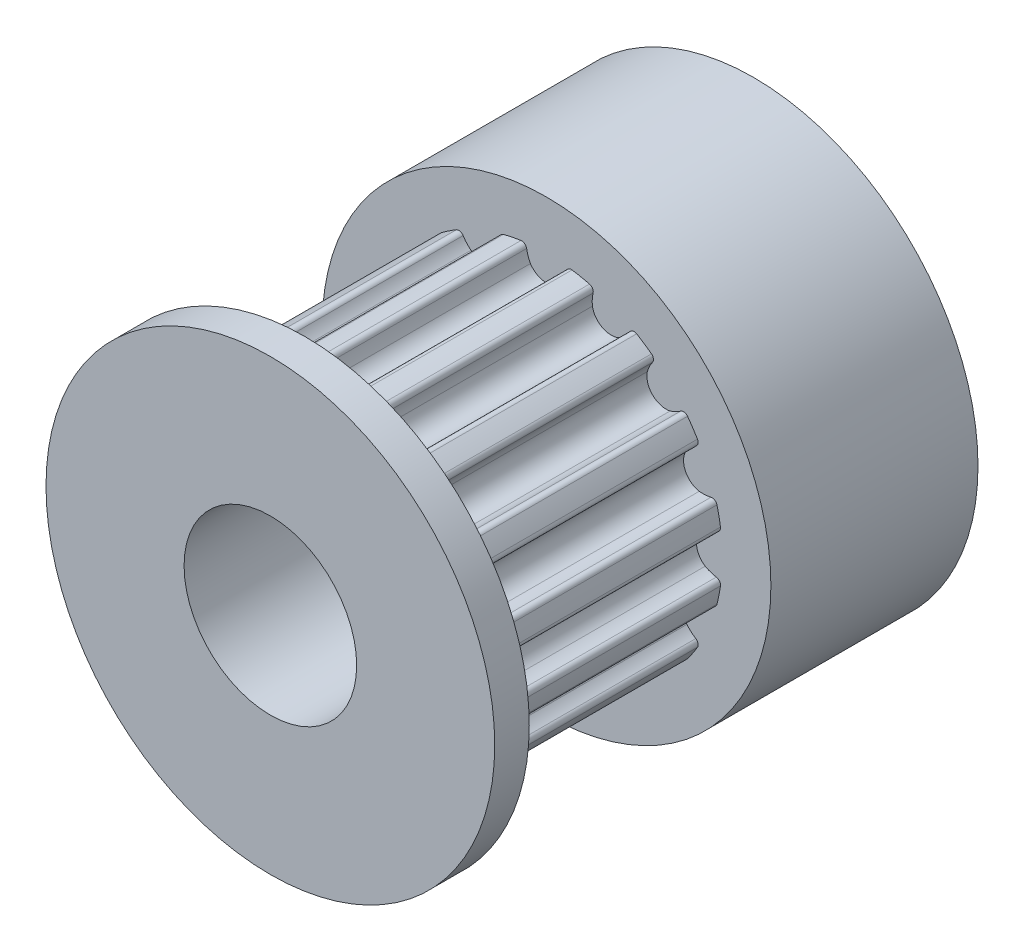
SolidWorks part; units mm, degrees
ref_plane "Front Plane" through (0, 0, 0) normal (0, 0, 1) x (1, 0, 0)
ref_plane "Top Plane" through (0, 0, 0) normal (0, 1, 0) x (1, 0, 0)
ref_plane "Right Plane" through (0, 0, 0) normal (1, 0, 0) x (0, 0, -1)
sketch "Sketch1" plane through (0, 0, 0) normal (0, 0, 1) x (1, 0, 0)
  circle A0 centre (0, 0) radius 6.5
  circle A1 centre (0, 0) radius 2.5
  dimension "D1" = 13
  dimension "D2" = 5
extrude "Boss-Extrude1" add sketch "Sketch1" along normal blind 14
ref_plane "Plane1" through (0, 0, 13) normal (0, 0, 1) x (1, 0, 0)
ref_plane "Plane2" through (0, 0, 6) normal (0, 0, -1) x (-1, 0, 0)
sketch "Sketch2" plane through (0, 0, 6) normal (0, 0, -1) x (-1, 0, 0)
  line L0 (1.949, 4.7053) -> (1.662, 4.0124) construction
  line L1 (3.6013, 3.6013) -> (3.0709, 3.0709) construction
  line L2 (4.7053, 1.949) -> (4.0124, 1.662) construction
  line L3 (0, 5.093) -> (0, 4.343) construction
  line L4 (5.093, 0) -> (4.343, 0) construction
  line L5 (4.7053, -1.949) -> (4.0124, -1.662) construction
  line L6 (3.6013, -3.6013) -> (3.0709, -3.0709) construction
  line L7 (1.949, -4.7053) -> (1.662, -4.0124) construction
  line L8 (0, -5.093) -> (0, -4.343) construction
  line L9 (-1.949, -4.7053) -> (-1.662, -4.0124) construction
  line L10 (-3.6013, -3.6013) -> (-3.0709, -3.0709) construction
  line L11 (-4.7053, -1.949) -> (-4.0124, -1.662) construction
  line L12 (-5.093, 0) -> (-4.343, 0) construction
  line L13 (-4.7053, 1.949) -> (-4.0124, 1.662) construction
  line L14 (-3.6013, 3.6013) -> (-3.0709, 3.0709) construction
  line L15 (-1.949, 4.7053) -> (-1.662, 4.0124) construction
  circle A0 centre (0, 0) radius 4.343 construction
  circle A2 centre (0, 0) radius 5.093 construction
  arc A3 (0.4659, 4.5964) -> (-0.4659, 4.5964) centre (0, 4.898) cw
  arc A4 (-0.4659, 4.5964) -> (-0.5762, 4.9194) centre (0.4114, 5.0763) cw
  arc A5 (-0.5762, 4.9194) -> (-0.739, 5.0391) centre (-0.7182, 4.8969) ccw
  arc A6 (-0.739, 5.0391) -> (-0.9936, 4.9951) centre (0, 0) ccw
  arc A8 (0.739, 5.0391) -> (0.9936, 4.9951) centre (0, 0) cw
  arc A9 (0.5762, 4.9194) -> (0.739, 5.0391) centre (0.7182, 4.8969) cw
  arc A10 (0.4659, 4.5964) -> (0.5762, 4.9194) centre (-0.4114, 5.0763) ccw
  arc A11 (2.1894, 4.0682) -> (1.3285, 4.4248) centre (1.8744, 4.5251) cw
  arc A12 (1.3285, 4.4248) -> (1.3502, 4.7655) centre (2.3227, 4.5325) cw
  arc A13 (1.3502, 4.7655) -> (1.2456, 4.9383) centre (1.2105, 4.7989) ccw
  arc A14 (1.2456, 4.9383) -> (0.9936, 4.9951) centre (0, 0) ccw
  arc A15 (2.6111, 4.3727) -> (2.8295, 4.2346) centre (0, 0) cw
  arc A16 (2.4149, 4.3244) -> (2.6111, 4.3727) centre (2.5374, 4.2493) cw
  arc A17 (2.1894, 4.0682) -> (2.4149, 4.3244) centre (1.5625, 4.8473) ccw
  arc A18 (3.5796, 2.9207) -> (2.9207, 3.5796) centre (3.4634, 3.4634) cw
  arc A19 (2.9207, 3.5796) -> (3.0711, 3.886) centre (3.8804, 3.2986) cw
  arc A20 (3.0711, 3.886) -> (3.0406, 4.0857) centre (2.9548, 3.9704) ccw
  arc A21 (3.0406, 4.0857) -> (2.8295, 4.2346) centre (0, 0) ccw
  arc A22 (4.0857, 3.0406) -> (4.2346, 2.8295) centre (0, 0) cw
  arc A23 (3.886, 3.0711) -> (4.0857, 3.0406) centre (3.9704, 2.9548) cw
  arc A24 (3.5796, 2.9207) -> (3.886, 3.0711) centre (3.2986, 3.8804) ccw
  arc A25 (4.4248, 1.3285) -> (4.0682, 2.1894) centre (4.5251, 1.8744) cw
  arc A26 (4.0682, 2.1894) -> (4.3244, 2.4149) centre (4.8473, 1.5625) cw
  arc A27 (4.3244, 2.4149) -> (4.3727, 2.6111) centre (4.2493, 2.5374) ccw
  arc A28 (4.3727, 2.6111) -> (4.2346, 2.8295) centre (0, 0) ccw
  arc A29 (4.9383, 1.2456) -> (4.9951, 0.9936) centre (0, 0) cw
  arc A30 (4.7655, 1.3502) -> (4.9383, 1.2456) centre (4.7989, 1.2105) cw
  arc A31 (4.4248, 1.3285) -> (4.7655, 1.3502) centre (4.5325, 2.3227) ccw
  arc A32 (4.5964, -0.4659) -> (4.5964, 0.4659) centre (4.898, 0) cw
  arc A33 (4.5964, 0.4659) -> (4.9194, 0.5762) centre (5.0763, -0.4114) cw
  arc A34 (4.9194, 0.5762) -> (5.0391, 0.739) centre (4.8969, 0.7182) ccw
  arc A35 (5.0391, 0.739) -> (4.9951, 0.9936) centre (0, 0) ccw
  arc A36 (5.0391, -0.739) -> (4.9951, -0.9936) centre (0, 0) cw
  arc A37 (4.9194, -0.5762) -> (5.0391, -0.739) centre (4.8969, -0.7182) cw
  arc A38 (4.5964, -0.4659) -> (4.9194, -0.5762) centre (5.0763, 0.4114) ccw
  arc A39 (4.0682, -2.1894) -> (4.4248, -1.3285) centre (4.5251, -1.8744) cw
  arc A40 (4.4248, -1.3285) -> (4.7655, -1.3502) centre (4.5325, -2.3227) cw
  arc A41 (4.7655, -1.3502) -> (4.9383, -1.2456) centre (4.7989, -1.2105) ccw
  arc A42 (4.9383, -1.2456) -> (4.9951, -0.9936) centre (0, 0) ccw
  arc A43 (4.3727, -2.6111) -> (4.2346, -2.8295) centre (0, 0) cw
  arc A44 (4.3244, -2.4149) -> (4.3727, -2.6111) centre (4.2493, -2.5374) cw
  arc A45 (4.0682, -2.1894) -> (4.3244, -2.4149) centre (4.8473, -1.5625) ccw
  arc A46 (2.9207, -3.5796) -> (3.5796, -2.9207) centre (3.4634, -3.4634) cw
  arc A47 (3.5796, -2.9207) -> (3.886, -3.0711) centre (3.2986, -3.8804) cw
  arc A48 (3.886, -3.0711) -> (4.0857, -3.0406) centre (3.9704, -2.9548) ccw
  arc A49 (4.0857, -3.0406) -> (4.2346, -2.8295) centre (0, 0) ccw
  arc A50 (3.0406, -4.0857) -> (2.8295, -4.2346) centre (0, 0) cw
  arc A51 (3.0711, -3.886) -> (3.0406, -4.0857) centre (2.9548, -3.9704) cw
  arc A52 (2.9207, -3.5796) -> (3.0711, -3.886) centre (3.8804, -3.2986) ccw
  arc A53 (1.3285, -4.4248) -> (2.1894, -4.0682) centre (1.8744, -4.5251) cw
  arc A54 (2.1894, -4.0682) -> (2.4149, -4.3244) centre (1.5625, -4.8473) cw
  arc A55 (2.4149, -4.3244) -> (2.6111, -4.3727) centre (2.5374, -4.2493) ccw
  arc A56 (2.6111, -4.3727) -> (2.8295, -4.2346) centre (0, 0) ccw
  arc A57 (1.2456, -4.9383) -> (0.9936, -4.9951) centre (0, 0) cw
  arc A58 (1.3502, -4.7655) -> (1.2456, -4.9383) centre (1.2105, -4.7989) cw
  arc A59 (1.3285, -4.4248) -> (1.3502, -4.7655) centre (2.3227, -4.5325) ccw
  arc A60 (-0.4659, -4.5964) -> (0.4659, -4.5964) centre (0, -4.898) cw
  arc A61 (0.4659, -4.5964) -> (0.5762, -4.9194) centre (-0.4114, -5.0763) cw
  arc A62 (0.5762, -4.9194) -> (0.739, -5.0391) centre (0.7182, -4.8969) ccw
  arc A63 (0.739, -5.0391) -> (0.9936, -4.9951) centre (0, 0) ccw
  arc A64 (-0.739, -5.0391) -> (-0.9936, -4.9951) centre (0, 0) cw
  arc A65 (-0.5762, -4.9194) -> (-0.739, -5.0391) centre (-0.7182, -4.8969) cw
  arc A66 (-0.4659, -4.5964) -> (-0.5762, -4.9194) centre (0.4114, -5.0763) ccw
  arc A67 (-2.1894, -4.0682) -> (-1.3285, -4.4248) centre (-1.8744, -4.5251) cw
  arc A68 (-1.3285, -4.4248) -> (-1.3502, -4.7655) centre (-2.3227, -4.5325) cw
  arc A69 (-1.3502, -4.7655) -> (-1.2456, -4.9383) centre (-1.2105, -4.7989) ccw
  arc A70 (-1.2456, -4.9383) -> (-0.9936, -4.9951) centre (0, 0) ccw
  arc A71 (-2.6111, -4.3727) -> (-2.8295, -4.2346) centre (0, 0) cw
  arc A72 (-2.4149, -4.3244) -> (-2.6111, -4.3727) centre (-2.5374, -4.2493) cw
  arc A73 (-2.1894, -4.0682) -> (-2.4149, -4.3244) centre (-1.5625, -4.8473) ccw
  arc A74 (-3.5796, -2.9207) -> (-2.9207, -3.5796) centre (-3.4634, -3.4634) cw
  arc A75 (-2.9207, -3.5796) -> (-3.0711, -3.886) centre (-3.8804, -3.2986) cw
  arc A76 (-3.0711, -3.886) -> (-3.0406, -4.0857) centre (-2.9548, -3.9704) ccw
  arc A77 (-3.0406, -4.0857) -> (-2.8295, -4.2346) centre (0, 0) ccw
  arc A78 (-4.0857, -3.0406) -> (-4.2346, -2.8295) centre (0, 0) cw
  arc A79 (-3.886, -3.0711) -> (-4.0857, -3.0406) centre (-3.9704, -2.9548) cw
  arc A80 (-3.5796, -2.9207) -> (-3.886, -3.0711) centre (-3.2986, -3.8804) ccw
  arc A81 (-4.4248, -1.3285) -> (-4.0682, -2.1894) centre (-4.5251, -1.8744) cw
  arc A82 (-4.0682, -2.1894) -> (-4.3244, -2.4149) centre (-4.8473, -1.5625) cw
  arc A83 (-4.3244, -2.4149) -> (-4.3727, -2.6111) centre (-4.2493, -2.5374) ccw
  arc A84 (-4.3727, -2.6111) -> (-4.2346, -2.8295) centre (0, 0) ccw
  arc A85 (-4.9383, -1.2456) -> (-4.9951, -0.9936) centre (0, 0) cw
  arc A86 (-4.7655, -1.3502) -> (-4.9383, -1.2456) centre (-4.7989, -1.2105) cw
  arc A87 (-4.4248, -1.3285) -> (-4.7655, -1.3502) centre (-4.5325, -2.3227) ccw
  arc A88 (-4.5964, 0.4659) -> (-4.5964, -0.4659) centre (-4.898, 0) cw
  arc A89 (-4.5964, -0.4659) -> (-4.9194, -0.5762) centre (-5.0763, 0.4114) cw
  arc A90 (-4.9194, -0.5762) -> (-5.0391, -0.739) centre (-4.8969, -0.7182) ccw
  arc A91 (-5.0391, -0.739) -> (-4.9951, -0.9936) centre (0, 0) ccw
  arc A92 (-5.0391, 0.739) -> (-4.9951, 0.9936) centre (0, 0) cw
  arc A93 (-4.9194, 0.5762) -> (-5.0391, 0.739) centre (-4.8969, 0.7182) cw
  arc A94 (-4.5964, 0.4659) -> (-4.9194, 0.5762) centre (-5.0763, -0.4114) ccw
  arc A95 (-4.0682, 2.1894) -> (-4.4248, 1.3285) centre (-4.5251, 1.8744) cw
  arc A96 (-4.4248, 1.3285) -> (-4.7655, 1.3502) centre (-4.5325, 2.3227) cw
  arc A97 (-4.7655, 1.3502) -> (-4.9383, 1.2456) centre (-4.7989, 1.2105) ccw
  arc A98 (-4.9383, 1.2456) -> (-4.9951, 0.9936) centre (0, 0) ccw
  arc A99 (-4.3727, 2.6111) -> (-4.2346, 2.8295) centre (0, 0) cw
  arc A100 (-4.3244, 2.4149) -> (-4.3727, 2.6111) centre (-4.2493, 2.5374) cw
  arc A101 (-4.0682, 2.1894) -> (-4.3244, 2.4149) centre (-4.8473, 1.5625) ccw
  arc A102 (-2.9207, 3.5796) -> (-3.5796, 2.9207) centre (-3.4634, 3.4634) cw
  arc A103 (-3.5796, 2.9207) -> (-3.886, 3.0711) centre (-3.2986, 3.8804) cw
  arc A104 (-3.886, 3.0711) -> (-4.0857, 3.0406) centre (-3.9704, 2.9548) ccw
  arc A105 (-4.0857, 3.0406) -> (-4.2346, 2.8295) centre (0, 0) ccw
  arc A106 (-3.0406, 4.0857) -> (-2.8295, 4.2346) centre (0, 0) cw
  arc A107 (-3.0711, 3.886) -> (-3.0406, 4.0857) centre (-2.9548, 3.9704) cw
  arc A108 (-2.9207, 3.5796) -> (-3.0711, 3.886) centre (-3.8804, 3.2986) ccw
  arc A109 (-1.3285, 4.4248) -> (-2.1894, 4.0682) centre (-1.8744, 4.5251) cw
  arc A110 (-2.1894, 4.0682) -> (-2.4149, 4.3244) centre (-1.5625, 4.8473) cw
  arc A111 (-2.4149, 4.3244) -> (-2.6111, 4.3727) centre (-2.5374, 4.2493) ccw
  arc A112 (-2.6111, 4.3727) -> (-2.8295, 4.2346) centre (0, 0) ccw
  arc A113 (-1.2456, 4.9383) -> (-0.9936, 4.9951) centre (0, 0) cw
  arc A114 (-1.3502, 4.7655) -> (-1.2456, 4.9383) centre (-1.2105, 4.7989) cw
  arc A115 (-1.3285, 4.4248) -> (-1.3502, 4.7655) centre (-2.3227, 4.5325) ccw
  circle A116 centre (0, 0) radius 6.5 construction
  circle A117 centre (0, 0) radius 6.5
  point P3 (0, 0)
  point P4 (0, 0)
  point P16 (-0.1625, 4.7008)
  point P23 (-1, 5.3336)
  point P27 (-1, 5.3206)
  point P28 (0, 4.6638)
  point P37 (-1.0553, 5.3052)
  point P52 (0, 5.4228)
  point P67 (-0.1625, 4.7045)
  point P82 (0.4896, 5.356)
  point P97 (-0.6742, 5.2356)
  point P112 (0.416, 4.8321)
  point P127 (0.4139, 4.8323)
  point P142 (0, 0)
  point P157 (-0.4659, 4.3534)
  point P172 (0, 0)
  point P187 (0.4081, 4.8328)
  point P202 (-0.7688, 4.5784)
  point P217 (-0.6969, 4.9019)
  point P232 (-0.5042, 4.6661)
  point P243 (-0.6881, 4.898)
  point P247 (-0.5676, 4.87)
  point P251 (0, 0)
  point P252 (0, 0)
  point P253 (-1, 5.3123)
  point P254 (-0.5078, 4.9866)
  point P255 (-0.5136, 5.0734)
  point P256 (-0.5852, 5.276)
  point P257 (-0.7482, 5.3626)
  point P258 (-1, 5.407)
  point P259 (-1, 5.407)
  point P260 (-0.5676, 4.87)
  point P261 (-0.5676, 4.87)
  point P262 (-0.7161, 4.898)
  point P263 (-0.5724, 4.8972)
  point P264 (-0.5762, 4.9194)
  dimension "D1" = 2
  dimension "D3" = 0.555
  dimension "D7" = 16
  dimension "D2" = 0.75
extrude "Cut-Extrude1" cut sketch "Sketch2" against normal up to surface (7 mm away)
